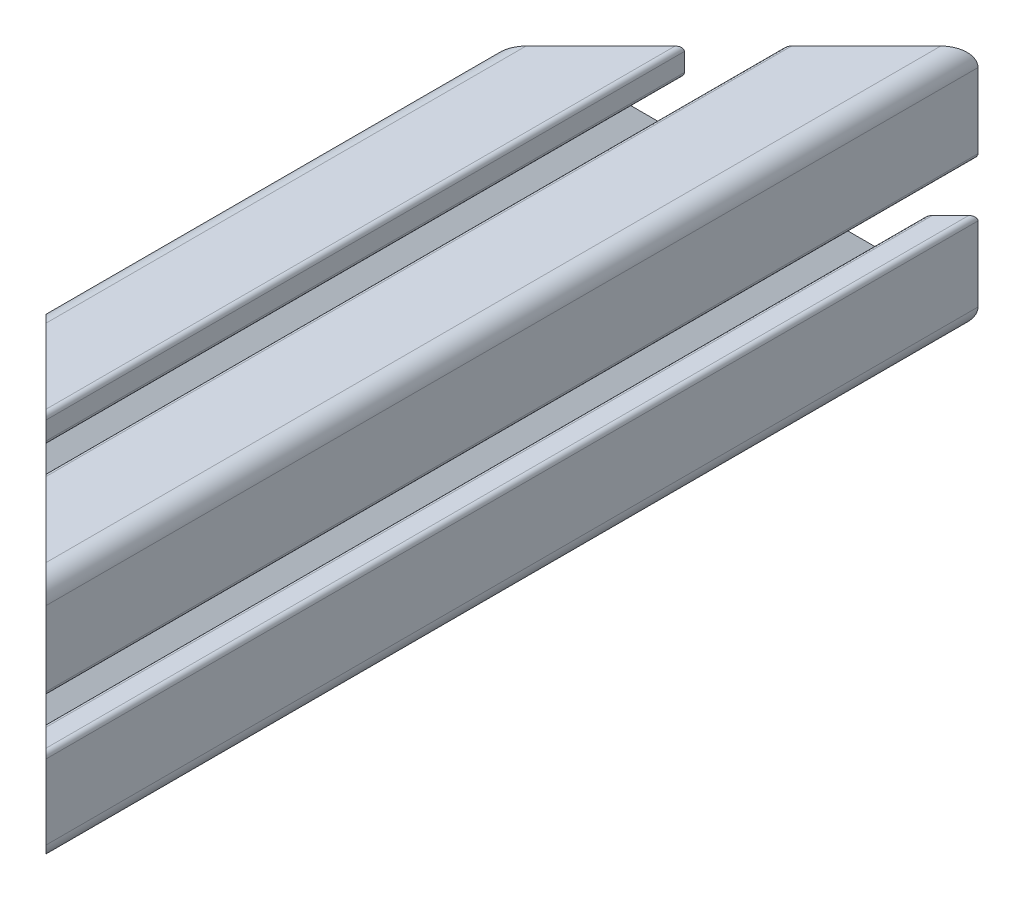
SolidWorks part; units mm, degrees
ref_plane "Front Plane" through (0, 0, 0) normal (0, 0, 1) x (1, 0, 0)
ref_plane "Top Plane" through (0, 0, 0) normal (0, 1, 0) x (1, 0, 0)
ref_plane "Right Plane" through (0, 0, 0) normal (1, 0, 0) x (0, 0, -1)
sketch "Sketch1" plane through (0, 0, 0) normal (0, 0, 1) x (1, 0, 0)
  line L0 (0, 20) -> (0, -20) construction
  line L1 (-20, 0) -> (20, 0) construction
  line L2 (-20, 16.952) -> (-20, 4.7625)
  line L3 (-16.952, 20) -> (-4.7625, 20)
  line L4 (-4.0005, 19.238) -> (-4.0005, 16.2662)
  line L5 (-4.7625, 15.5042) -> (-10.4856, 15.5042)
  line L6 (-11.0244, 14.2034) -> (-5.456, 8.6351)
  line L7 (-14.2034, 11.0244) -> (-8.6351, 5.456)
  line L8 (-15.5042, 10.4856) -> (-15.5042, 4.7625)
  line L9 (-16.2662, 4.0005) -> (-19.238, 4.0005)
  line L10 (0, 0) -> (-20, 20) construction
  line L11 (-3.3367, 7.7572) -> (3.3367, 7.7572)
  line L12 (-7.7572, 3.3367) -> (-7.7572, -3.3367)
  line L13 (16.2662, 4.0005) -> (19.238, 4.0005)
  line L14 (15.5042, 10.4856) -> (15.5042, 4.7625)
  line L15 (20, 16.952) -> (20, 4.7625)
  line L16 (16.952, 20) -> (4.7625, 20)
  line L17 (4.0005, 19.238) -> (4.0005, 16.2662)
  line L18 (4.7625, 15.5042) -> (10.4856, 15.5042)
  line L19 (7.7572, 3.3367) -> (7.7572, -3.3367)
  line L20 (11.0244, 14.2034) -> (5.456, 8.6351)
  line L21 (14.2034, 11.0244) -> (8.6351, 5.456)
  line L22 (-16.2662, -4.0005) -> (-19.238, -4.0005)
  line L23 (-15.5042, -10.4856) -> (-15.5042, -4.7625)
  line L24 (-14.2034, -11.0244) -> (-8.6351, -5.456)
  line L25 (-11.0244, -14.2034) -> (-5.456, -8.6351)
  line L26 (-4.7625, -15.5042) -> (-10.4856, -15.5042)
  line L27 (-4.0005, -19.238) -> (-4.0005, -16.2662)
  line L28 (-16.952, -20) -> (-4.7625, -20)
  line L29 (-20, -16.952) -> (-20, -4.7625)
  line L30 (20, -16.952) -> (20, -4.7625)
  line L31 (16.952, -20) -> (4.7625, -20)
  line L32 (4.0005, -19.238) -> (4.0005, -16.2662)
  line L33 (4.7625, -15.5042) -> (10.4856, -15.5042)
  line L34 (11.0244, -14.2034) -> (5.456, -8.6351)
  line L35 (14.2034, -11.0244) -> (8.6351, -5.456)
  line L36 (15.5042, -10.4856) -> (15.5042, -4.7625)
  line L37 (16.2662, -4.0005) -> (19.238, -4.0005)
  line L38 (-3.3367, -7.7572) -> (3.3367, -7.7572)
  circle A0 centre (0, 0) radius 3.4036
  arc A1 (-20, 16.952) -> (-16.952, 20) centre (-16.952, 16.952) cw
  arc A2 (-14.2034, 11.0244) -> (-15.5042, 10.4856) centre (-14.7422, 10.4856) ccw
  arc A3 (-10.4856, 15.5042) -> (-11.0244, 14.2034) centre (-10.4856, 14.7422) ccw
  arc A4 (-4.7625, 20) -> (-4.0005, 19.238) centre (-4.7625, 19.238) cw
  arc A5 (-20, 4.7625) -> (-19.238, 4.0005) centre (-19.238, 4.7625) ccw
  arc A6 (-15.5042, 4.7625) -> (-16.2662, 4.0005) centre (-16.2662, 4.7625) cw
  arc A7 (-4.0005, 16.2662) -> (-4.7625, 15.5042) centre (-4.7625, 16.2662) cw
  arc A8 (-3.3367, 7.7572) -> (-5.456, 8.6351) centre (-3.3367, 10.7544) cw
  arc A9 (-7.7572, 3.3367) -> (-8.6351, 5.456) centre (-10.7544, 3.3367) ccw
  arc A10 (15.5042, 4.7625) -> (16.2662, 4.0005) centre (16.2662, 4.7625) ccw
  arc A11 (20, 4.7625) -> (19.238, 4.0005) centre (19.238, 4.7625) cw
  arc A12 (20, 16.952) -> (16.952, 20) centre (16.952, 16.952) ccw
  arc A13 (4.7625, 20) -> (4.0005, 19.238) centre (4.7625, 19.238) ccw
  arc A14 (4.0005, 16.2662) -> (4.7625, 15.5042) centre (4.7625, 16.2662) ccw
  arc A15 (3.3367, 7.7572) -> (5.456, 8.6351) centre (3.3367, 10.7544) ccw
  arc A16 (7.7572, 3.3367) -> (8.6351, 5.456) centre (10.7544, 3.3367) cw
  arc A17 (14.2034, 11.0244) -> (15.5042, 10.4856) centre (14.7422, 10.4856) cw
  arc A18 (10.4856, 15.5042) -> (11.0244, 14.2034) centre (10.4856, 14.7422) cw
  arc A19 (-7.7572, -3.3367) -> (-8.6351, -5.456) centre (-10.7544, -3.3367) cw
  arc A20 (-3.3367, -7.7572) -> (-5.456, -8.6351) centre (-3.3367, -10.7544) ccw
  arc A21 (-4.0005, -16.2662) -> (-4.7625, -15.5042) centre (-4.7625, -16.2662) ccw
  arc A22 (-15.5042, -4.7625) -> (-16.2662, -4.0005) centre (-16.2662, -4.7625) ccw
  arc A23 (-20, -4.7625) -> (-19.238, -4.0005) centre (-19.238, -4.7625) cw
  arc A24 (-4.7625, -20) -> (-4.0005, -19.238) centre (-4.7625, -19.238) ccw
  arc A25 (-10.4856, -15.5042) -> (-11.0244, -14.2034) centre (-10.4856, -14.7422) cw
  arc A26 (-14.2034, -11.0244) -> (-15.5042, -10.4856) centre (-14.7422, -10.4856) cw
  arc A27 (-20, -16.952) -> (-16.952, -20) centre (-16.952, -16.952) ccw
  arc A28 (20, -16.952) -> (16.952, -20) centre (16.952, -16.952) cw
  arc A29 (14.2034, -11.0244) -> (15.5042, -10.4856) centre (14.7422, -10.4856) ccw
  arc A30 (10.4856, -15.5042) -> (11.0244, -14.2034) centre (10.4856, -14.7422) ccw
  arc A31 (4.7625, -20) -> (4.0005, -19.238) centre (4.7625, -19.238) cw
  arc A32 (20, -4.7625) -> (19.238, -4.0005) centre (19.238, -4.7625) ccw
  arc A33 (15.5042, -4.7625) -> (16.2662, -4.0005) centre (16.2662, -4.7625) cw
  arc A34 (4.0005, -16.2662) -> (4.7625, -15.5042) centre (4.7625, -16.2662) cw
  arc A35 (3.3367, -7.7572) -> (5.456, -8.6351) centre (3.3367, -10.7544) cw
  arc A36 (7.7572, -3.3367) -> (8.6351, -5.456) centre (10.7544, -3.3367) ccw
  point P29 (-20, 4.0005)
  point P32 (-15.5042, 4.0005)
  point P36 (-4.5782, 7.7572)
  point P68 (0, 7.7572)
  dimension "D4" = 6.8072
  dimension "D5" = 3.048
  dimension "D6" = 0.762
  dimension "D9" = 0.762
  dimension "D10" = 0.762
  dimension "D11" = 4.4958
  dimension "D13" = 2.9972
  dimension "D1" = 40
  dimension "D2" = 40
  dimension "D3" = 12.2428
  dimension "D7" = 8.001
  dimension "D8" = 4.4958
extrude "Extrude1" add sketch "Sketch1" along normal mid plane 152.4
ref_plane "Plane1" through (0, 16.952, 0) normal (0, 1, 0) x (1, 0, 0)
sketch "Sketch3" plane through (0, 16.952, 0) normal (0, 1, 0) x (1, 0, 0)
  line L0 (20, -76.2) -> (-20, -36.2)
  line L1 (-20, -76.2) -> (-20, 76.2) construction
  line L2 (-20, -36.2) -> (-20, -76.2)
  line L3 (-20, -76.2) -> (20, -76.2)
  dimension "D1" = 45
extrude "Cut-Extrude1" cut sketch "Sketch3" against normal through all
sketch "Sketch4" plane through (0, 16.952, 0) normal (0, -1, 0) x (-1, 0, 0)
  line L0 (20, -36.2) -> (-20, -76.2)
  line L1 (-20, -76.2) -> (20, -76.2)
  line L2 (20, -76.2) -> (20, -36.2)
extrude "Cut-Extrude2" cut sketch "Sketch4" against normal through all
sketch "Sketch5" plane through (0, 16.952, 0) normal (0, 1, 0) x (1, 0, 0)
  line L0 (20, 76.2) -> (-20, 76.2)
  line L1 (-20, -36.2) -> (-20, 76.2) construction
  line L3 (-20, 76.2) -> (-20, 36.2)
  line L4 (-20, 36.2) -> (20, 76.2)
  dimension "D1" = 45
extrude "Cut-Extrude3" cut sketch "Sketch5" against normal up to next
sketch "Sketch7" plane through (0, 16.952, 0) normal (0, -1, 0) x (-1, 0, 0)
  line L0 (20, 36.2) -> (20, 76.2)
  line L1 (20, 76.2) -> (-20, 76.2)
  line L2 (-20, 76.2) -> (20, 36.2)
extrude "Cut-Extrude5" cut sketch "Sketch7" against normal through all
equation "\"D2@Sketch1\" = \"D1@Sketch1\""
